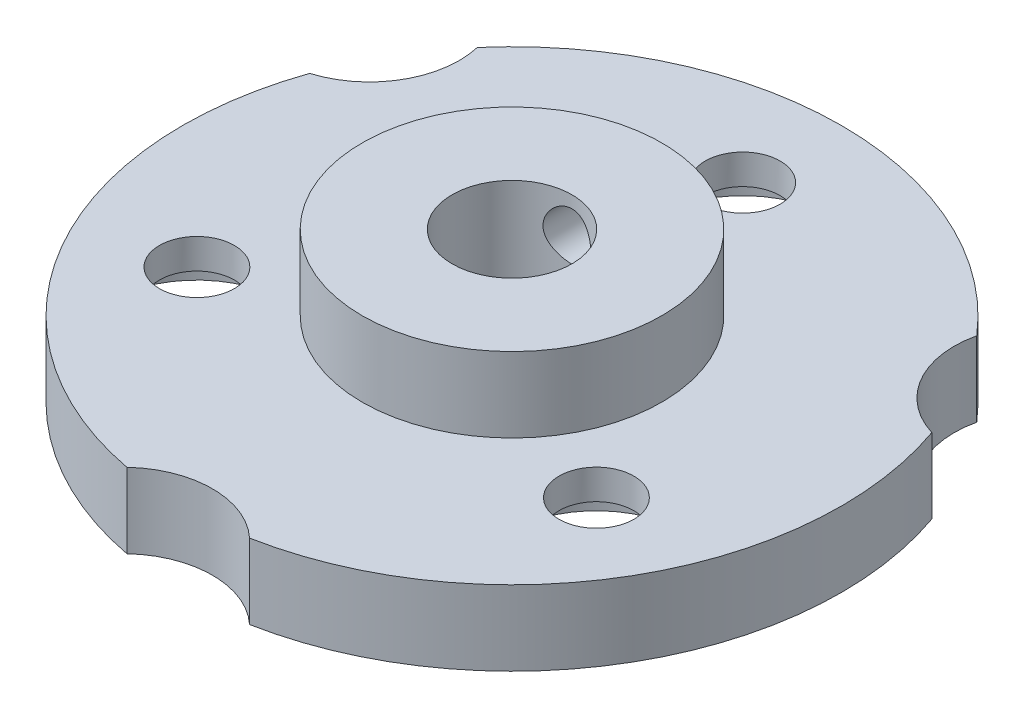
SolidWorks part; units mm, degrees
ref_plane "Plano frontal" through (0, 0, 0) normal (0, 0, 1) x (1, 0, 0)
ref_plane "Plano superior" through (0, 0, 0) normal (0, 1, 0) x (1, 0, 0)
ref_plane "Plano direito" through (0, 0, 0) normal (1, 0, 0) x (0, 0, -1)
sketch "Esboço1" plane through (0, 0, 0) normal (0, 1, 0) x (1, 0, 0)
  circle A0 centre (0, 0) radius 11
  dimension "D1" = 22
extrude "Ressalto-extrusão1" add sketch "Esboço1" along normal blind 2.5
sketch "Esboço3" plane through (0, 2.5, 0) normal (0, 1, 0) x (1, 0, 0)
  circle A1 centre (0, 7.7) radius 1.25
  circle A2 centre (6.6684, -3.85) radius 1.25
  circle A3 centre (-6.6684, -3.85) radius 1.25
  dimension "D3" = 2.5
  dimension "D1" = 7.7
  dimension "D2" = 7.7
extrude "Corte-extrusão1" cut sketch "Esboço3" against normal blind 2.5
sketch "Esboço18" plane through (0, 2.5, 0) normal (0, 1, 0) x (1, 0, 0)
  circle A0 centre (0, 0) radius 5
  dimension "D1" = 10
extrude "Ressalto-extrusão5" add sketch "Esboço18" along normal blind 2.5
sketch "Esboço20" plane through (0, 5, 0) normal (0, 1, 0) x (1, 0, 0)
  circle A0 centre (0, 0) radius 2
  dimension "D1" = 4
extrude "Corte-extrusão5" cut sketch "Esboço20" against normal blind 5.5
hole_wizard "Broca de rosquear para tarraxa de M2x0.42" positions "3DSketch3" profile "Esboço21" hole size "M2x0.4" standard "Ansi Metric"
sketch3d "3DSketch3"
  point P0 (0.0026, 3.793, -5)
sketch "Esboço21" plane through (0.0026, 3.793, -5) normal (0, 1, 0) x (-1, 0, -0.0005)
  line L0 (0, 0) -> (0, 3)
  line L1 (0, 3) -> (0.8, 3)
  line L2 (0.8, 3) -> (0.8, 0)
  line L5 (0.8, 0) -> (0, 0)
  line L11 (0, -6.35) -> (0, 107.95) construction
  dimension "Thru Hole Dia." = 1.6
  dimension "Thru Hole Depth" = 3
sketch "Esboço22" plane through (0, 2.5, 0) normal (0, 1, 0) x (1, 0, 0)
  circle A1 centre (-11.2583, 6.5) radius 3
  circle A2 centre (0, -13) radius 3
  circle A3 centre (11.2583, 6.5) radius 3
  dimension "D1" = 6
extrude "Corte-extrusão6" cut sketch "Esboço22" against normal blind 5.5
sketch "Esboço23" plane through (0, 0, 0) normal (0, -1, 0) x (-1, 0, 0)
  circle A0 centre (-6.6684, -3.85) radius 3
  circle A1 centre (6.6684, -3.85) radius 3
  circle A2 centre (0, 7.7) radius 3
  dimension "D1" = 6
extrude "Corte-extrusão7" cut sketch "Esboço23" against normal blind 1.5
